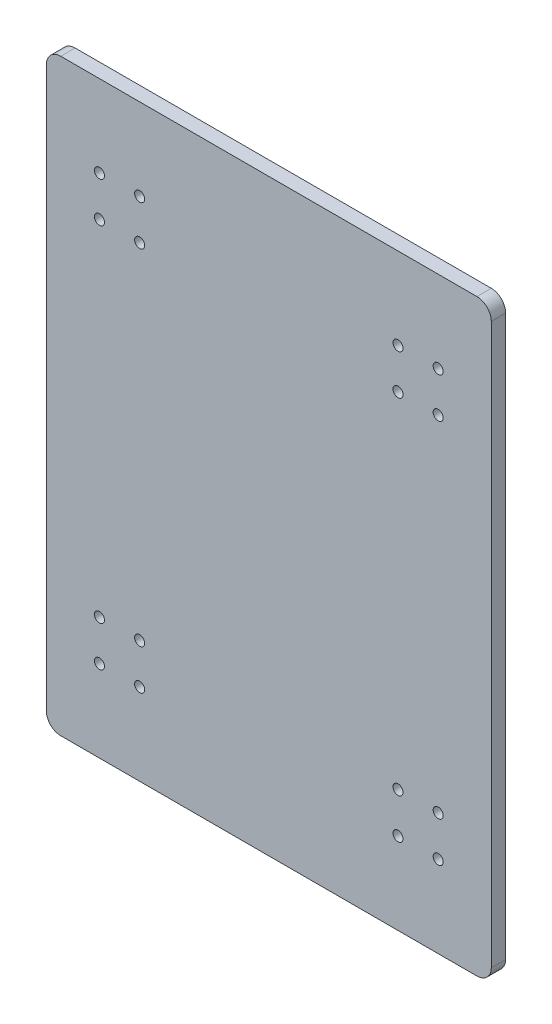
SolidWorks part; units mm, degrees
material "6063-O"
ref_plane "正面" through (0, 0, 0) normal (0, 0, 1) x (1, 0, 0)
ref_plane "平面" through (0, 0, 0) normal (0, 1, 0) x (1, 0, 0)
ref_plane "右側面" through (0, 0, 0) normal (1, 0, 0) x (0, 0, -1)
sketch "ｽｹｯﾁ1" plane through (0, 0, 0) normal (0, 0, 1) x (1, 0, 0)
  line L1 (-77.5, 102.5) -> (77.5, 102.5)
  line L2 (-77.5, 102.5) -> (-77.5, -102.5)
  line L3 (-77.5, -102.5) -> (77.5, -102.5)
  line L4 (77.5, 102.5) -> (77.5, -102.5)
  line L5 (-77.5, 102.5) -> (77.5, -102.5) construction
  line L6 (-77.5, -102.5) -> (77.5, 102.5) construction
  point P0 (0, 0)
  dimension "D1" = 155
  dimension "D2" = 205
extrude "ﾎﾞｽ - 押し出し1" add sketch "ｽｹｯﾁ1" along normal blind 5
sketch "ｽｹｯﾁ2" plane through (0, 0, 5) normal (0, 0, 1) x (1, 0, 0)
  line L0 (45, 74) -> (45, 60) construction
  line L1 (45, 60) -> (59, 60) construction
  line L2 (59, 60) -> (59, 74) construction
  line L3 (59, 74) -> (45, 74) construction
  circle A0 centre (45, 74) radius 1.75
  circle A1 centre (59, 74) radius 1.75
  circle A2 centre (45, 60) radius 1.75
  circle A3 centre (59, 60) radius 1.75
  dimension "D5" = 3.5
  dimension "D6" = 3.5
  dimension "D7" = 3.5
  dimension "D8" = 3.5
  dimension "D1" = 14
  dimension "D2" = 14
  dimension "D3" = 45
  dimension "D4" = 60
extrude "ｶｯﾄ - 押し出し1" cut sketch "ｽｹｯﾁ2" against normal through all
mirror "ﾐﾗｰ1" about plane through (0, 0, 0) normal (0, 1, 0) of "ｶｯﾄ - 押し出し1"
mirror "ﾐﾗｰ2" about plane through (0, 0, 0) normal (1, 0, 0) of "ﾐﾗｰ1", "ｶｯﾄ - 押し出し1"
fillet "ﾌｨﾚｯﾄ1" radius 5 4 edges at (-77.5, -102.5, 2.5) (77.5, -102.5, 2.5) (77.5, 102.5, 2.5) (-77.5, 102.5, 2.5)
